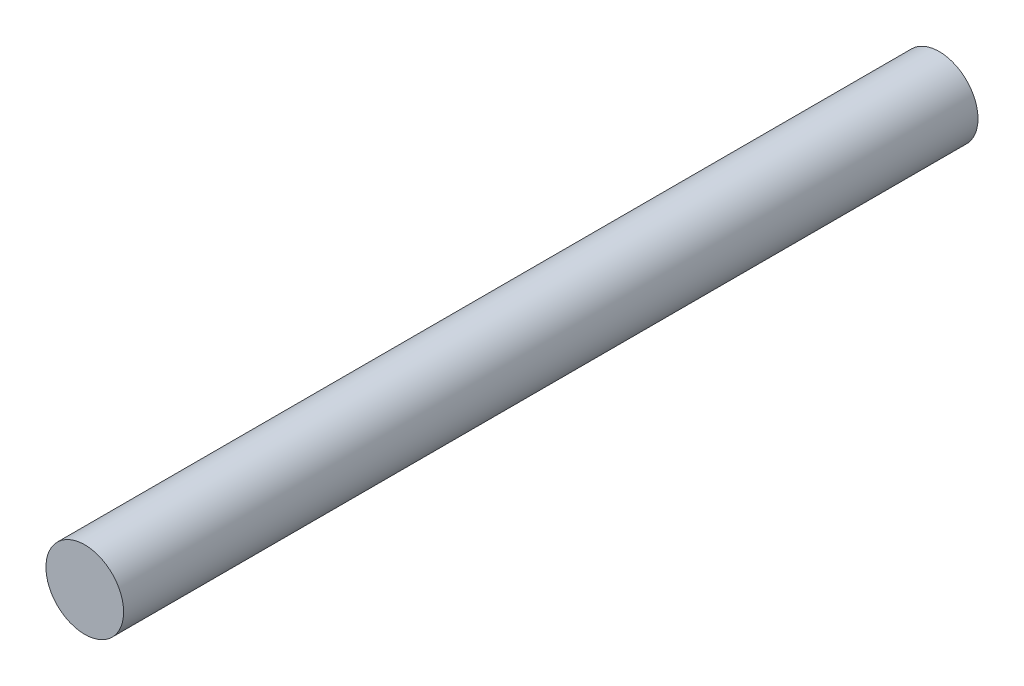
SolidWorks part; units mm, degrees
ref_plane "前视基准面" through (0, 0, 0) normal (0, 0, 1) x (1, 0, 0)
ref_plane "上视基准面" through (0, 0, 0) normal (0, 1, 0) x (1, 0, 0)
ref_plane "右视基准面" through (0, 0, 0) normal (1, 0, 0) x (0, 0, -1)
sketch "草图1" plane through (0, 0, 0) normal (0, 0, 1) x (1, 0, 0)
  circle A0 centre (0, 0) radius 5
  dimension "D1" = 10
extrude "凸台-拉伸1" add sketch "草图1" along normal blind 110
